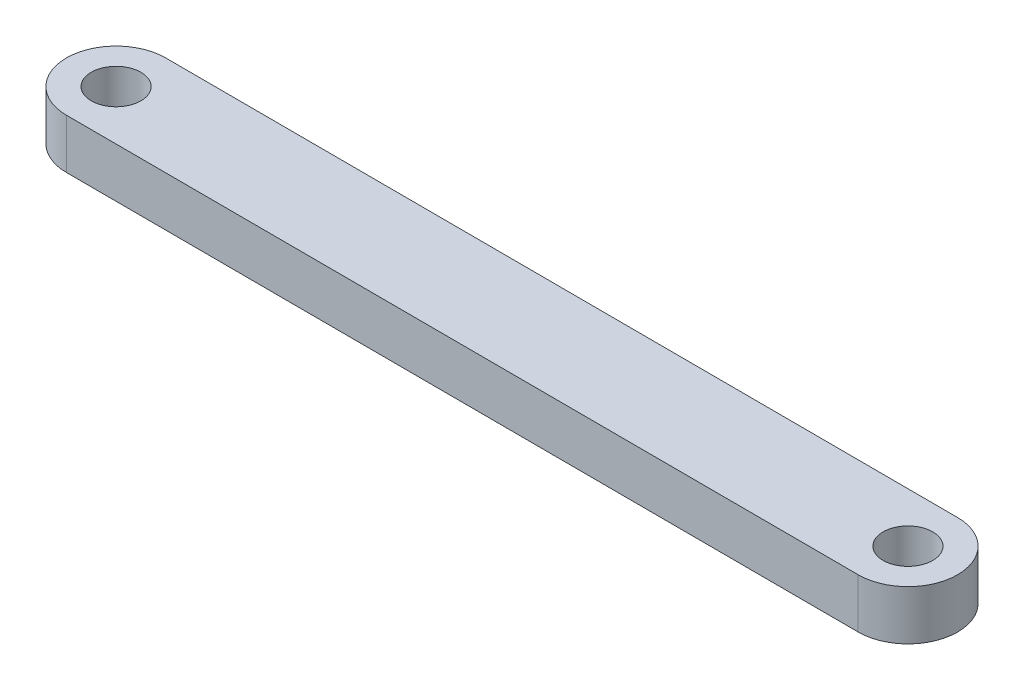
SolidWorks part; units mm, degrees
ref_plane "Front Plane" through (0, 0, 0) normal (0, 0, 1) x (1, 0, 0)
ref_plane "Top Plane" through (0, 0, 0) normal (0, 1, 0) x (1, 0, 0)
ref_plane "Right Plane" through (0, 0, 0) normal (1, 0, 0) x (0, 0, -1)
sketch "Sketch2" plane through (0, 0, 0) normal (0, 1, 0) x (1, 0, 0)
  line L0 (-0.6806, -3.3395) -> (79.3194, -3.5505) construction
  line L1 (-0.6674, 1.6604) -> (79.3326, 1.4495)
  line L2 (-0.6938, -8.3395) -> (79.3062, -8.5505)
  arc A0 (-0.6674, 1.6604) -> (-0.6938, -8.3395) centre (-0.6806, -3.3395) ccw
  arc A1 (79.3062, -8.5505) -> (79.3326, 1.4495) centre (79.3194, -3.5505) ccw
  point P2 (39.3194, -3.445)
  dimension "D1" = 80
  dimension "D2" = 10
extrude "Boss-Extrude1" add sketch "Sketch2" along normal blind 5
sketch "Sketch3" plane through (0, 5, 0) normal (0, 1, 0) x (1, 0, 0)
  line L0 (79.3326, 1.4495) -> (-0.6674, 1.6604) construction
  circle A0 centre (-0.6806, -3.3395) radius 2.5
  circle A1 centre (79.3194, -3.5505) radius 2.5
  arc A2 (79.3062, -8.5505) -> (79.3326, 1.4495) centre (79.3194, -3.5505) ccw construction
  point P9 (84.3194, -3.5637)
  dimension "D1" = 5
  dimension "D2" = 5
  dimension "D3" = 80
  dimension "D4" = 5
  dimension "D5" = 5
  dimension "D6" = 5
extrude "Cut-Extrude1" cut sketch "Sketch3" against normal up to next
